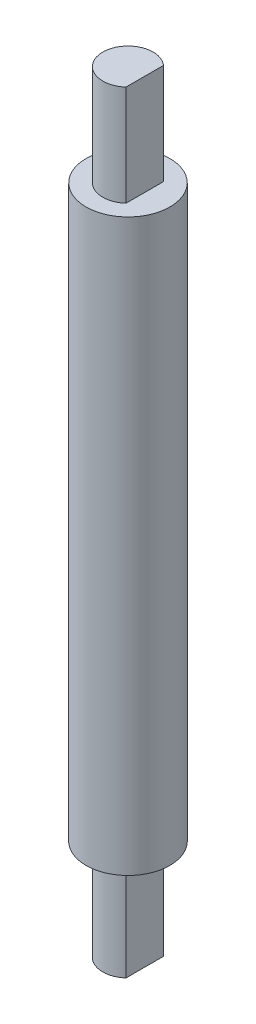
SolidWorks part; units mm, degrees
ref_plane "前视基准面" through (0, 0, 0) normal (0, 0, 1) x (1, 0, 0)
ref_plane "上视基准面" through (0, 0, 0) normal (0, 1, 0) x (1, 0, 0)
ref_plane "右视基准面" through (0, 0, 0) normal (1, 0, 0) x (0, 0, -1)
sketch "草图1" plane through (0, 0, 0) normal (0, 1, 0) x (1, 0, 0)
  circle A0 centre (0, 0) radius 2.5
extrude "凸台-拉伸1" add sketch "草图1" along normal blind 34
sketch "草图2" plane through (0, 34, 0) normal (0, 1, 0) x (1, 0, 0)
  line L0 (0, 0) -> (1, 0) construction
  line L1 (1, 1.118) -> (1, -1.118)
  arc A1 (1, -1.118) -> (1, 1.118) centre (0, 0) cw
extrude "凸台-拉伸2" add sketch "草图2" along normal blind 6
sketch "草图3" plane through (0, 0, 0) normal (0, -1, 0) x (1, 0, 0)
  line L0 (0, 0) -> (1, 0) construction
  line L1 (1, -1.118) -> (1, 1.118)
  arc A1 (1, -1.118) -> (1, 1.118) centre (0, 0) cw
extrude "凸台-拉伸3" add sketch "草图3" along normal blind 6
